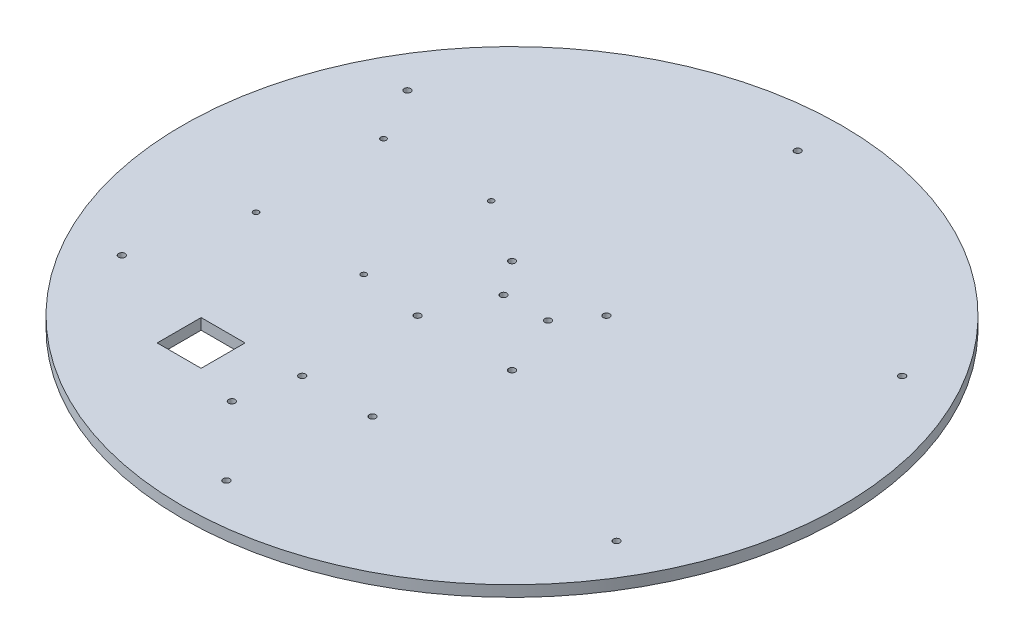
SolidWorks part; units mm, degrees
ref_plane "Front Plane" through (0, 0, 0) normal (0, 0, 1) x (1, 0, 0)
ref_plane "Top Plane" through (0, 0, 0) normal (0, 1, 0) x (1, 0, 0)
ref_plane "Right Plane" through (0, 0, 0) normal (1, 0, 0) x (0, 0, -1)
sketch "Sketch1" plane through (0, 0, 0) normal (0, 1, 0) x (1, 0, 0)
  circle A0 centre (0, 0) radius 150
  dimension "D1" = 300
extrude "Boss-Extrude1" add sketch "Sketch1" along normal blind 5
sketch "Sketch2" plane through (0, 5, 0) normal (0, 1, 0) x (1, 0, 0)
  circle A0 centre (0, 130) radius 1.5
  circle A1 centre (112.5833, 65) radius 1.5
  circle A2 centre (112.5833, -65) radius 1.5
  circle A3 centre (0, -130) radius 1.5
  circle A4 centre (-112.5833, -65) radius 1.5
  circle A5 centre (-112.5833, 65) radius 1.5
  point P2 (0, 0)
  point P4 (0, 0)
  point P5 (0, 0)
  point P10 (0, 0)
  dimension "D1" = 3
  dimension "D2" = 130
  dimension "D3" = 6
extrude "Cut-Extrude1" cut sketch "Sketch2" against normal blind 5
sketch "Sketch3" plane through (0, 5, 0) normal (0, 1, 0) x (1, 0, 0)
  circle A0 centre (-10.1, 6.25) radius 1.5
  circle A1 centre (10.1, 6.25) radius 1.5
  point P4 (-18.1003, 14.8376)
  point P5 (-10.2556, 14.6)
  dimension "D1" = 3
  dimension "D2" = 3
  dimension "D3" = 20.2
  dimension "D4" = 6.25
  dimension "D5" = 10.1
extrude "Cut-Extrude2" cut sketch "Sketch3" against normal blind 5
sketch "Sketch4" plane through (0, 5, 0) normal (0, 1, 0) x (1, 0, 0)
  circle A0 centre (-21.5, 21.5) radius 1.5
  circle A1 centre (21.5, 21.5) radius 1.5
  circle A2 centre (-21.5, -21.5) radius 1.5
  circle A3 centre (21.5, -21.5) radius 1.5
  point P13 (0, 0)
  dimension "D1" = 3
  dimension "D2" = 43
  dimension "D3" = 43
  dimension "D4" = 21.5
  dimension "D5" = 21.5
extrude "Cut-Extrude3" cut sketch "Sketch4" against normal blind 5
sketch "Sketch5" plane through (0, 5, 0) normal (0, 1, 0) x (1, 0, 0)
  line L1 (-35, -53.5) -> (35, -53.5) construction
  line L2 (-35, -53.5) -> (-35, -109.5) construction
  line L3 (-35, -109.5) -> (35, -109.5) construction
  line L4 (35, -53.5) -> (35, -109.5) construction
  line L5 (-35, -53.5) -> (35, -109.5) construction
  line L6 (-35, -109.5) -> (35, -53.5) construction
  line L7 (-70, -71.5) -> (-50, -71.5)
  line L8 (-70, -71.5) -> (-70, -91.5)
  line L9 (-70, -91.5) -> (-50, -91.5)
  line L10 (-50, -71.5) -> (-50, -91.5)
  line L11 (-70, -71.5) -> (-50, -91.5) construction
  line L12 (-70, -91.5) -> (-50, -71.5) construction
  circle A0 centre (-21.5, -21.5) radius 1.5 construction
  circle A1 centre (-30, -97.5) radius 1.5
  circle A2 centre (-24, -71.5) radius 1.5
  circle A3 centre (8, -71.5) radius 1.5
  point P0 (0, -81.5)
  point P14 (-60, -81.5)
  dimension "D4" = 3
  dimension "D1" = 70
  dimension "D2" = 56
  dimension "D3" = 60
  dimension "D5" = 5
  dimension "D6" = 12
  dimension "D7" = 6
  dimension "D8" = 26
  dimension "D9" = 32
  dimension "D10" = 20
  dimension "D11" = 20
  dimension "D12" = 15
extrude "Cut-Extrude4" cut sketch "Sketch5" against normal blind 5
sketch "Sketch6" plane through (0, 5, 0) normal (0, 1, 0) x (1, 0, 0)
  line L1 (-102.5, 44) -> (-46.5, 44) construction
  line L2 (-102.5, 44) -> (-102.5, -44) construction
  line L3 (-102.5, -44) -> (-46.5, -44) construction
  line L4 (-46.5, 44) -> (-46.5, -44) construction
  line L5 (-102.5, 44) -> (-46.5, -44) construction
  line L6 (-102.5, -44) -> (-46.5, 44) construction
  circle A0 centre (-21.5, 21.5) radius 1.5 construction
  circle A1 centre (-50, 40.5) radius 1.25
  circle A2 centre (-99, 40.5) radius 1.25
  circle A3 centre (-99, -17.5) radius 1.25
  circle A4 centre (-50, -17.5) radius 1.25
  point P0 (-74.5, 0)
  point P18 (-131.2551, 46.7474)
  dimension "D4" = 2.5
  dimension "D1" = 56
  dimension "D2" = 88
  dimension "D3" = 25
  dimension "D5" = 3.5
  dimension "D6" = 3.5
  dimension "D7" = 49
  dimension "D8" = 58
extrude "Cut-Extrude5" cut sketch "Sketch6" against normal blind 5
